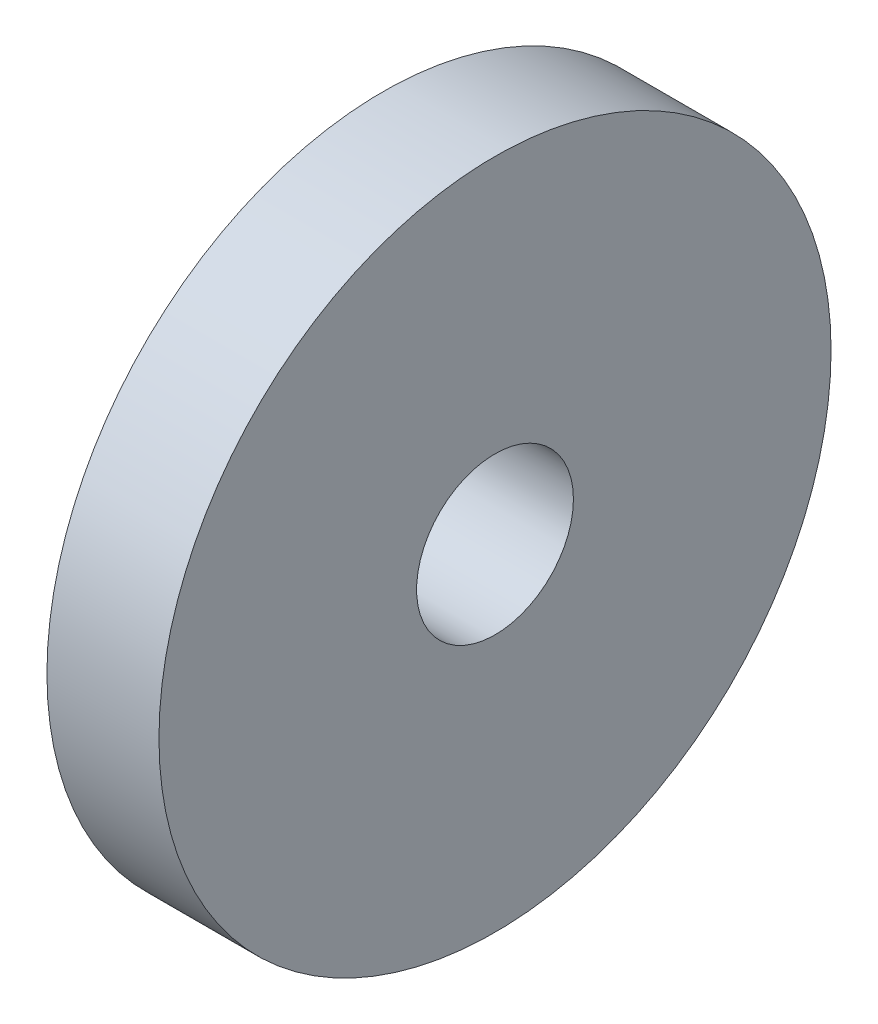
SolidWorks part; units mm, degrees
material "ASTM A36 Steel"
ref_plane "Front Plane" through (0, 0, 0) normal (0, 0, 1) x (1, 0, 0)
ref_plane "Top Plane" through (0, 0, 0) normal (0, 1, 0) x (1, 0, 0)
ref_plane "Right Plane" through (0, 0, 0) normal (1, 0, 0) x (0, 0, -1)
sketch "Sketch1" plane through (0, 0, 0) normal (1, 0, 0) x (0, 0, -1)
  circle A0 centre (0, 0) radius 30
  circle A1 centre (0, 0) radius 7
  dimension "D1" = 60
  dimension "D2" = 14
extrude "Boss-Extrude1" add sketch "Sketch1" along normal mid plane 10
